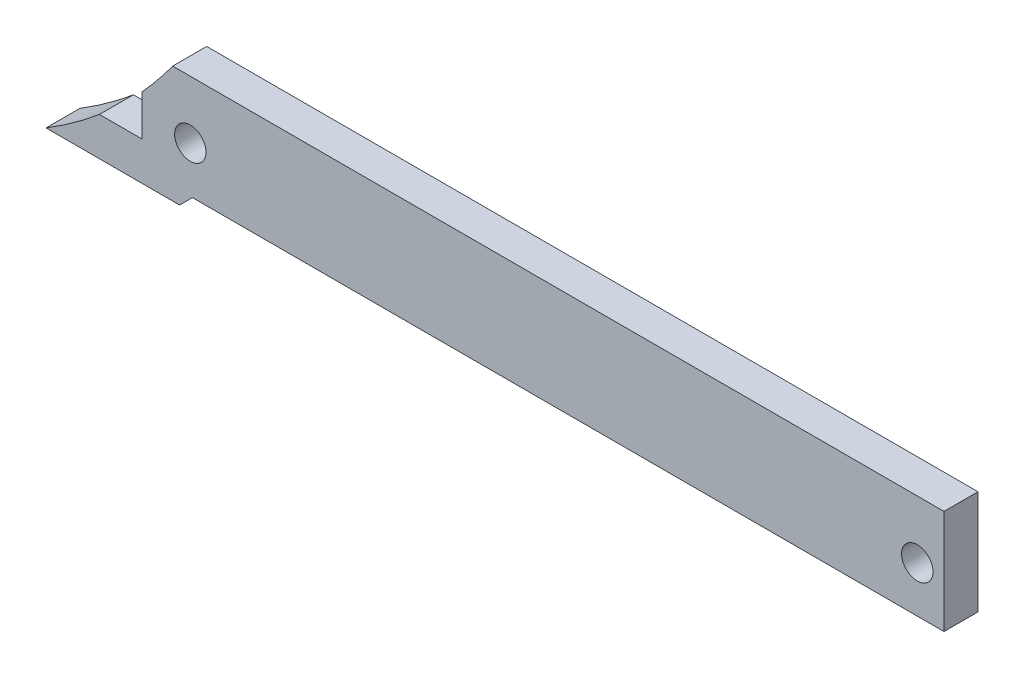
SolidWorks part; units mm, degrees
ref_plane "Front Plane" through (0, 0, 0) normal (0, 0, 1) x (1, 0, 0)
ref_plane "Top Plane" through (0, 0, 0) normal (0, 1, 0) x (1, 0, 0)
ref_plane "Right Plane" through (0, 0, 0) normal (1, 0, 0) x (0, 0, -1)
sketch "Sketch1" plane through (0, 0, 0) normal (0, 0, 1) x (1, 0, 0)
  line L0 (75, 1.9322) -> (11.9646, 1.9223) construction
  line L2 (0, 0) -> (0, 3.84)
  line L3 (0, 3.84) -> (75, 3.84)
  line L4 (75, 0.0244) -> (75, 3.84)
  line L5 (0, 0) -> (0, -0.0825)
  line L6 (0, -0.0825) -> (-4, -0.0825)
  line L7 (-9, -3.6773) -> (3.5, -3.6773)
  line L8 (3.5, -3.6773) -> (4.7017, -2.4756)
  line L9 (75, 0.0244) -> (75, -2.4756)
  line L10 (75, -2.4756) -> (4.7017, -2.4756)
  circle A0 centre (72.5, 1.84) radius 1.47
  arc A1 (-4, -0.0825) -> (-9, -3.6773) centre (-30.5121, 31.5192) cw
  dimension "D3" = 2.94
  dimension "D4" = 2.5
  dimension "D5" = 2
  dimension "D7" = 5
  dimension "D1" = 3.84
  dimension "D2" = 75
  dimension "D6" = 70.2983
  dimension "D8" = 135
  dimension "D9" = 12.5
  dimension "D10" = 2.5
extrude "Boss-Extrude1" add sketch "Sketch1" along normal blind 3.18
sketch "Sketch3" plane through (0, 0, 3.18) normal (0, 0, 1) x (1, 0, 0)
  line L0 (75, 3.84) -> (0, 3.84) construction
  line L1 (0, 3.84) -> (0, -0.0825) construction
  circle A2 centre (4.5, 1.84) radius 1.47
  dimension "D1" = 2.94
  dimension "D2" = 2
  dimension "D3" = 4.5
extrude "Cut-Extrude1" cut sketch "Sketch3" against normal through all
sketch "Sketch4" plane through (0, 3.84, 0) normal (0, 1, 0) x (1, 0, 0)
  line L1 (0, 0) -> (75, 0)
  line L2 (0, 0) -> (0, -3.18)
  line L3 (0, -3.18) -> (75, -3.18)
  line L4 (75, 0) -> (75, -3.18)
extrude "Cut-Extrude2" cut sketch "Sketch4" against normal up to surface (0.08 mm away)
sketch "Sketch6" plane through (0, 0, 0) normal (0, 0, -1) x (-1, 0, 0)
  line L0 (-2.8503, 7.26) -> (-75, 7.26)
  line L1 (-75, 7.26) -> (-75, 3.76)
  line L2 (-75, 3.76) -> (0, 3.76)
  arc A0 (0, 3.76) -> (-2.8503, 7.26) centre (30.5121, 31.5192) cw
  dimension "D1" = 3.5
extrude "Boss-Extrude2" add sketch "Sketch6" against normal up to surface (3.18 mm away) contours L0 L1 L2 A0 up to face at (5.97, 1.84, 3.18)
